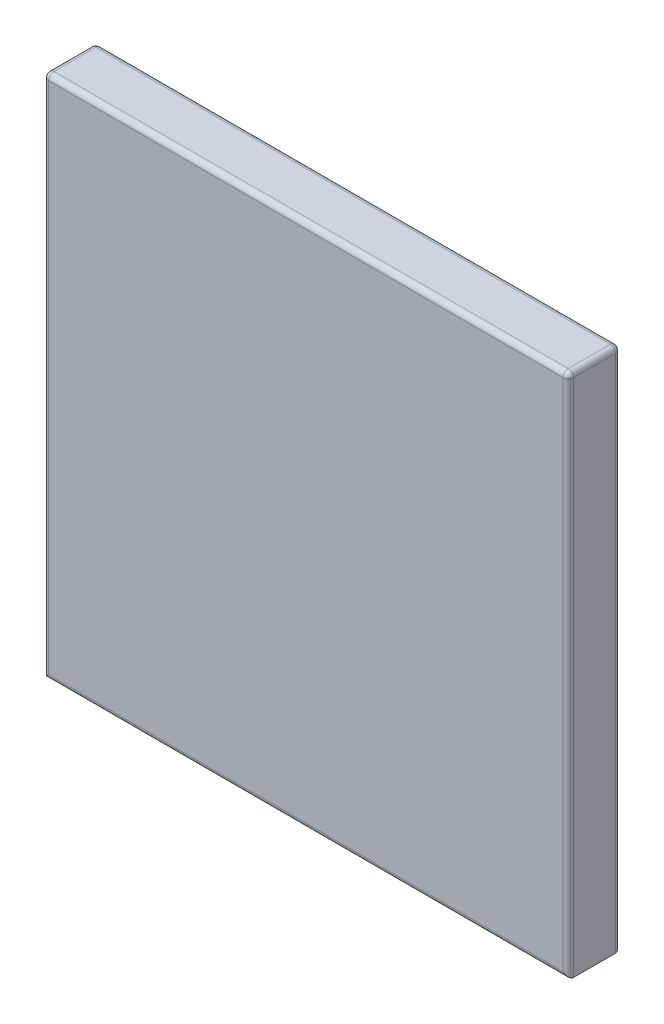
SolidWorks part; units mm, degrees
ref_plane "Front Plane" through (0, 0, 0) normal (0, 0, 1) x (1, 0, 0)
ref_plane "Top Plane" through (0, 0, 0) normal (0, 1, 0) x (1, 0, 0)
ref_plane "Right Plane" through (0, 0, 0) normal (1, 0, 0) x (0, 0, -1)
sketch "Sketch1" plane through (0, 0, 0) normal (0, 0, 1) x (1, 0, 0)
  line L1 (-50, 50) -> (50, 50)
  line L2 (-50, 50) -> (-50, -50)
  line L3 (-50, -50) -> (50, -50)
  line L4 (50, 50) -> (50, -50)
  line L5 (-50, 50) -> (50, -50) construction
  line L6 (-50, -50) -> (50, 50) construction
  point P0 (0, 0)
  point P6 (49.9884, 49.7844)
  point P8 (0, 0)
  point P9 (-50, 49.7177)
  point P10 (50.0123, -49.9877)
  point P11 (-49.1871, -50)
  point P12 (-50.2649, -49.7323)
  point P13 (49.6499, -50)
  point P14 (-49.8151, 49.8152)
  point P15 (49.8362, 50)
  dimension "D1" = 100
  dimension "D2" = 100
extrude "Boss-Extrude1" add sketch "Sketch1" along normal blind 10
fillet "Fillet2" radius 1 1 edges at (0, 50, 10)
fillet "Fillet3" radius 1 1 edges at (0, 50, 0)
fillet "Fillet5" radius 1 12 edges at (50, 49.7071, 0.2929) (50, 50, 5) (50, 49.7071, 9.7071) (-50, 49.7071, 0.2929) (-50, 50, 5) (-50, 49.7071, 9.7071) (0, -50, 0) (50, -0.5, 0) (50, -0.5, 10) (0, -50, 10) (-50, -0.5, 0) (-50, -0.5, 10)
